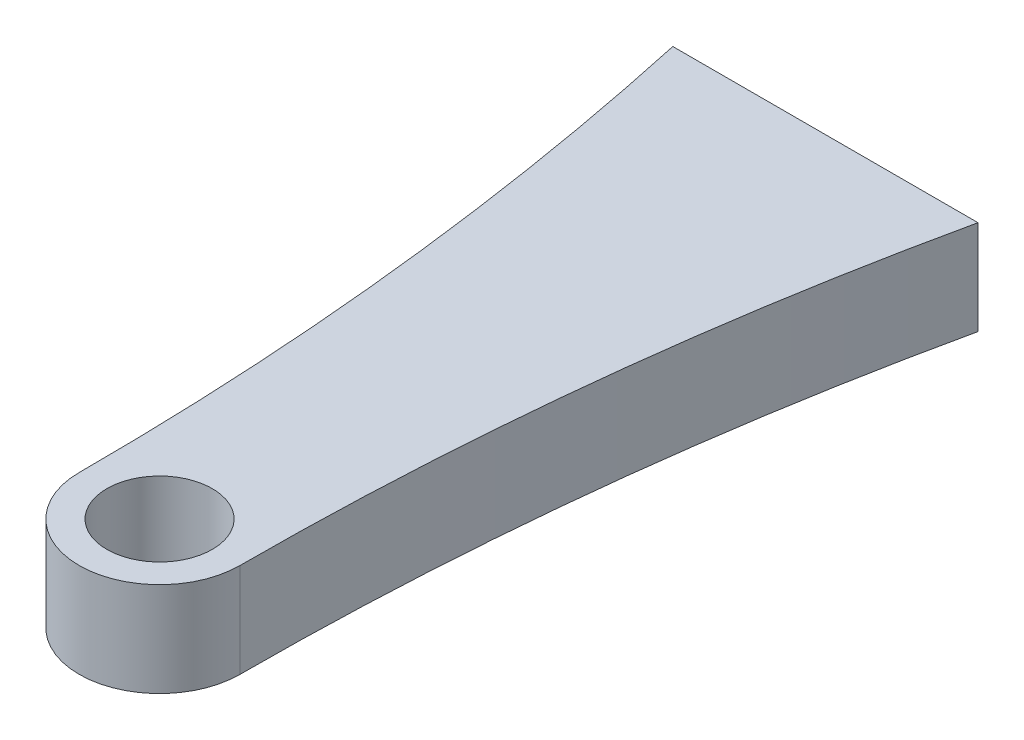
SolidWorks part; units mm, degrees
ref_plane "Front Plane" through (0, 0, 0) normal (0, 0, 1) x (1, 0, 0)
ref_plane "Top Plane" through (0, 0, 0) normal (0, 1, 0) x (1, 0, 0)
ref_plane "Right Plane" through (0, 0, 0) normal (1, 0, 0) x (0, 0, -1)
sketch "Sketch1" plane through (0, 0, 0) normal (0, 1, 0) x (1, 0, 0)
  line L0 (-34.925, 152.4) -> (34.925, 152.4)
  line L1 (0, 0) -> (0, 152.4) construction
  circle A0 centre (0, 0) radius 12.065
  circle A1 centre (0, 0) radius 152.4 construction
  arc A2 (-18.415, 0) -> (18.415, 0) centre (0, 0) ccw
  arc A3 (-34.925, 152.4) -> (-18.415, 0) centre (-730.0546, 0) cw
  arc A4 (34.925, 152.4) -> (18.415, 0) centre (730.0546, 0) ccw
  circle A6 centre (0, 0) radius 18.415 construction
  point P7 (0, 152.4)
  point P14 (18.0975, 0)
  dimension "D1" = 24.13
  dimension "D2" = 152.4
  dimension "D4" = 69.85
  dimension "D3" = 6.35
extrude "Boss-Extrude1" add sketch "Sketch1" along normal mid plane 21.59
sketch "Sketch3" plane through (0, 0, -152.4) normal (0, 0, -1) x (-1, 0, 0)
  line L0 (-1000, 0) -> (49000, 0) construction
  line L1 (0, -15.5111) -> (0, 15.5111) construction
  circle A0 centre (-25.4, 0) radius 3.175
  circle A1 centre (25.4, 0) radius 3.175
  point P6 (0, 0)
  dimension "D1" = 6.35
  dimension "D2" = 25.4
